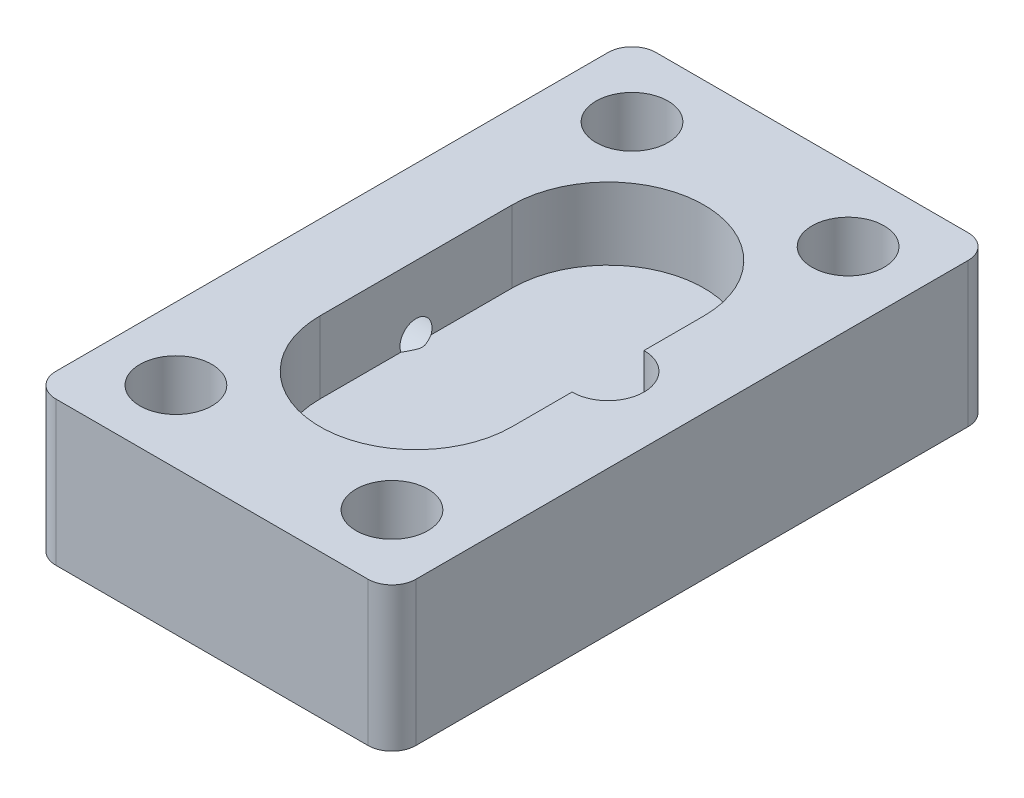
SolidWorks part; units mm, degrees
ref_plane "Front Plane" through (0, 0, 0) normal (0, 0, 1) x (1, 0, 0)
ref_plane "Top Plane" through (0, 0, 0) normal (0, 1, 0) x (1, 0, 0)
ref_plane "Right Plane" through (0, 0, 0) normal (1, 0, 0) x (0, 0, -1)
sketch "Sketch1" plane through (0, 0, 0) normal (0, 1, 0) x (1, 0, 0)
  line L1 (-7.5, -12.5) -> (7.5, -12.5)
  line L2 (-7.5, -12.5) -> (-7.5, 12.5)
  line L3 (-7.5, 12.5) -> (7.5, 12.5)
  line L4 (7.5, -12.5) -> (7.5, 12.5)
  line L5 (-7.5, -12.5) -> (7.5, 12.5) construction
  line L6 (-7.5, 12.5) -> (7.5, -12.5) construction
  point P0 (0, 0)
  dimension "D1" = 25
  dimension "D2" = 15
extrude "Boss-Extrude1" add sketch "Sketch1" along normal blind 6
sketch "Sketch2" plane through (0, 6, 0) normal (0, 1, 0) x (1, 0, 0)
  line L0 (0, 4) -> (0, -4) construction
  line L1 (4, 4) -> (4, 1.5)
  line L2 (-4, 4) -> (-4, -4)
  line L3 (4, -1.5) -> (4, -4)
  arc A0 (4, 4) -> (-4, 4) centre (0, 4) ccw
  arc A1 (-4, -4) -> (4, -4) centre (0, -4) ccw
  arc A2 (4, -1.5) -> (4, 1.5) centre (4, 0) ccw
  point P3 (0, 0)
  point P10 (0, 0)
  point P12 (0, 4.939)
  point P13 (0, 0)
  point P14 (0, 0)
  dimension "D2" = 8
  dimension "D3" = 1.5
  dimension "D4" = 4
  dimension "D1" = 8
extrude "Cut-Extrude1" cut sketch "Sketch2" against normal blind 3
sketch "Sketch3" plane through (0, 6, 0) normal (0, 1, 0) x (1, 0, 0)
  line L0 (-4.5, 9.5) -> (4.5, -9.5) construction
  line L2 (-4.5, -9.5) -> (4.5, 9.5) construction
  circle A0 centre (-4.5, 9.5) radius 1.5
  circle A1 centre (4.5, 9.5) radius 1.5
  circle A2 centre (-4.5, -9.5) radius 1.5
  circle A3 centre (4.5, -9.5) radius 1.5
  point P8 (0, 0)
  dimension "D1" = 3
  dimension "D3" = 9
  dimension "D4" = 19
extrude "Cut-Extrude2" cut sketch "Sketch3" against normal through all
sketch "Sketch4" plane through (0, 0, 0) normal (0, -1, 0) x (1, 0, 0)
  circle A0 centre (4, 0) radius 2.5
  point P2 (0, 0)
  dimension "D1" = 5
  dimension "D2" = 4
extrude "Cut-Extrude3" cut sketch "Sketch4" against normal blind 3
hole_wizard "Ø3.0mm Dowel Hole1" positions "Sketch6" profile "Sketch5" hole size "Ø3.0" standard "ANSI Metric"
sketch "Sketch6" plane through (-7.5, 0, 0) normal (-1, 0, 0) x (0, 0, 1)
  point P0 (0, 3.2305)
  point P2 (0, 0)
sketch "Sketch5" plane through (-7.5, 3.2305, 0) normal (0, 1, 0) x (0, 0, 1)
  line L0 (0, 0) -> (0, 3.9013)
  line L1 (0, 3.9013) -> (1.5, 3)
  line L2 (1.5, 3) -> (1.5, 0)
  line L5 (1.5, 0) -> (0, 0)
  line L10 (0, 3.9013) -> (-1.5, 3) construction
  line L11 (0, -6.35) -> (0, 107.95) construction
  dimension "Hole Dia." = 3
  dimension "Hole Depth" = 3
  dimension "Drill Angle" = 118
sketch "Sketch7" plane through (-7.5, 0, 0) normal (-1, 0, 0) x (0, 0, 1)
  circle A0 centre (0, 3.2305) radius 2.5
  dimension "D1" = 5
extrude "Cut-Extrude4" cut sketch "Sketch7" against normal blind 1.5
fillet "Fillet1" radius 1 4 edges at (-7.5, 3, -12.5) (-7.5, 3, 12.5) (7.5, 3, 12.5) (7.5, 3, -12.5)
